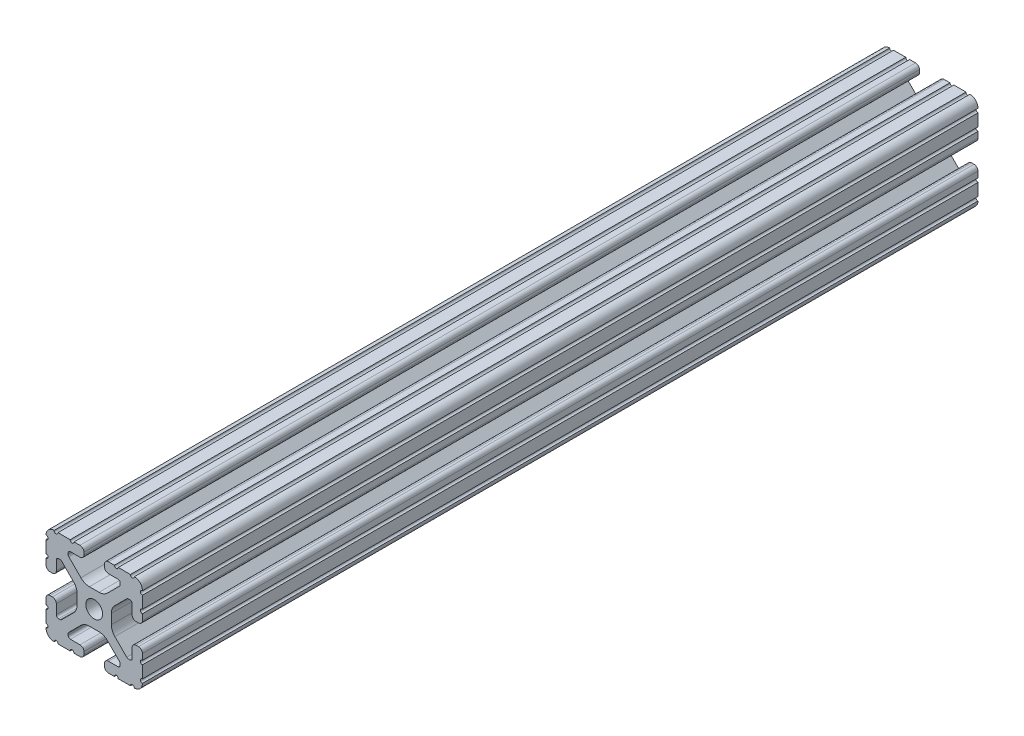
SolidWorks part; units mm, degrees
material "6061 Alloy"
ref_plane "Front Plane" through (0, 0, 0) normal (0, 0, 1) x (1, 0, 0)
ref_plane "Top Plane" through (0, 0, 0) normal (0, 1, 0) x (1, 0, 0)
ref_plane "Right Plane" through (0, 0, 0) normal (1, 0, 0) x (0, 0, -1)
sketch "Sketch1" plane through (0, 0, 0) normal (0, 0, 1) x (1, 0, 0)
  line L0 (0, 25.6181) -> (0, -24.623) construction
  line L1 (-20.8943, 0) -> (20.4607, 0) construction
  line L2 (-10.0229, 12.9148) -> (-5.2522, 8.144)
  line L3 (-10.287, 14.0843) -> (-10.287, 13.5524)
  line L4 (-5.6176, 14.986) -> (-9.3853, 14.986)
  line L5 (-4.064, 17.4964) -> (-4.064, 16.5396)
  line L6 (-7.9742, 19.05) -> (-5.6176, 19.05)
  line L7 (-14.3277, 19.05) -> (-9.4982, 19.05)
  line L8 (-19.05, 9.4961) -> (-19.05, 14.3277)
  line L9 (-19.05, 5.6176) -> (-19.05, 7.9763)
  line L10 (-16.5396, 4.064) -> (-17.4964, 4.064)
  line L11 (-14.986, 9.3853) -> (-14.986, 5.6176)
  line L12 (-13.516, 10.287) -> (-14.0843, 10.287)
  line L13 (-8.1476, 5.2921) -> (-12.8784, 10.0229)
  line L14 (-6.7564, -1.9335) -> (-6.7564, 1.9335)
  line L15 (-12.8784, -10.0229) -> (-8.1476, -5.2921)
  line L16 (-14.0843, -10.287) -> (-13.516, -10.287)
  line L17 (-14.986, -5.6176) -> (-14.986, -9.3853)
  line L18 (-17.4964, -4.064) -> (-16.5396, -4.064)
  line L19 (-19.05, -7.9763) -> (-19.05, -5.6176)
  line L20 (-19.05, -14.3277) -> (-19.05, -9.4961)
  line L21 (-9.4961, -19.05) -> (-14.3277, -19.05)
  line L22 (-5.6176, -19.05) -> (-7.9763, -19.05)
  line L23 (-4.064, -17.4964) -> (-4.064, -16.5396)
  line L24 (10.0229, -12.9148) -> (5.2522, -8.144)
  line L25 (10.287, -14.0843) -> (10.287, -13.5524)
  line L26 (5.6176, -14.986) -> (9.3853, -14.986)
  line L28 (-1.9022, 6.7564) -> (1.9022, 6.7564)
  line L29 (-1.9022, -6.7564) -> (1.9022, -6.7564)
  line L31 (-5.6176, -14.986) -> (-9.3853, -14.986)
  line L32 (-10.287, -14.0843) -> (-10.287, -13.5524)
  line L33 (-10.0229, -12.9148) -> (-5.2522, -8.144)
  line L66 (4.064, -16.5396) -> (4.064, -17.4964)
  line L67 (5.6176, -19.05) -> (7.9763, -19.05)
  line L68 (9.4961, -19.05) -> (14.3277, -19.05)
  line L69 (19.05, -14.3277) -> (19.05, -9.4961)
  line L70 (19.05, -7.9763) -> (19.05, -5.6176)
  line L71 (17.4964, -4.064) -> (16.5396, -4.064)
  line L72 (14.986, -5.6176) -> (14.986, -9.3853)
  line L73 (14.0843, -10.287) -> (13.516, -10.287)
  line L74 (12.8784, -10.0229) -> (8.1476, -5.2921)
  line L75 (6.7564, -1.9335) -> (6.7564, 1.9335)
  line L76 (8.1476, 5.2921) -> (12.8784, 10.0229)
  line L77 (13.516, 10.287) -> (14.0843, 10.287)
  line L78 (14.986, 9.3853) -> (14.986, 5.6176)
  line L79 (16.5396, 4.064) -> (17.4964, 4.064)
  line L80 (19.05, 5.6176) -> (19.05, 7.9763)
  line L81 (19.05, 9.4961) -> (19.05, 14.3277)
  line L82 (14.3277, 19.05) -> (9.4982, 19.05)
  line L83 (7.9742, 19.05) -> (5.6176, 19.05)
  line L84 (4.064, 17.4964) -> (4.064, 16.5396)
  line L85 (5.6176, 14.986) -> (9.3853, 14.986)
  line L86 (10.287, 14.0843) -> (10.287, 13.5524)
  line L87 (10.0229, 12.9148) -> (5.2522, 8.144)
  arc A0 (-10.0229, 12.9148) -> (-10.287, 13.5524) centre (-9.3853, 13.5524) cw
  circle A1 centre (0, 0) radius 3.3274
  arc A2 (-10.287, 14.0843) -> (-9.3853, 14.986) centre (-9.3853, 14.0843) cw
  arc A3 (-4.064, 16.5396) -> (-5.6176, 14.986) centre (-5.6176, 16.5396) cw
  arc A4 (-5.6176, 19.05) -> (-4.064, 17.4964) centre (-5.6176, 17.4964) cw
  arc A5 (-7.9742, 19.05) -> (-9.4982, 19.05) centre (-8.7362, 19.05) cw
  arc A6 (-14.3277, 19.05) -> (-15.8475, 19.05) centre (-15.0876, 18.9933) cw
  arc A7 (-19.05, 15.8475) -> (-15.8475, 19.05) centre (-15.8751, 15.8751) cw
  arc A8 (-19.05, 15.8475) -> (-19.05, 14.3277) centre (-18.9933, 15.0876) cw
  arc A9 (-19.05, 9.4961) -> (-19.05, 7.9763) centre (-18.9933, 8.7362) cw
  arc A10 (-17.4964, 4.064) -> (-19.05, 5.6176) centre (-17.4964, 5.6176) cw
  arc A11 (-14.986, 5.6176) -> (-16.5396, 4.064) centre (-16.5396, 5.6176) cw
  arc A12 (-14.986, 9.3853) -> (-14.0843, 10.287) centre (-14.0843, 9.3853) cw
  arc A13 (-13.516, 10.287) -> (-12.8784, 10.0229) centre (-13.516, 9.3853) cw
  arc A14 (-8.1476, 5.2921) -> (-6.7564, 1.9335) centre (-11.5062, 1.9335) cw
  arc A15 (-6.7564, -1.9335) -> (-8.1476, -5.2921) centre (-11.5062, -1.9335) cw
  arc A16 (-12.8784, -10.0229) -> (-13.516, -10.287) centre (-13.516, -9.3853) cw
  arc A17 (-14.0843, -10.287) -> (-14.986, -9.3853) centre (-14.0843, -9.3853) cw
  arc A18 (-16.5396, -4.064) -> (-14.986, -5.6176) centre (-16.5396, -5.6176) cw
  arc A19 (-19.05, -5.6176) -> (-17.4964, -4.064) centre (-17.4964, -5.6176) cw
  arc A20 (-19.05, -7.9763) -> (-19.05, -9.4961) centre (-18.9933, -8.7362) cw
  arc A21 (-19.05, -14.3277) -> (-19.05, -15.8475) centre (-18.9933, -15.0876) cw
  arc A22 (-15.8475, -19.05) -> (-19.05, -15.8475) centre (-15.8751, -15.8751) cw
  arc A23 (-15.8475, -19.05) -> (-14.3277, -19.05) centre (-15.0876, -18.9933) cw
  arc A24 (-9.4961, -19.05) -> (-7.9763, -19.05) centre (-8.7362, -18.9933) cw
  arc A25 (-4.064, -17.4964) -> (-5.6176, -19.05) centre (-5.6176, -17.4964) cw
  arc A26 (-5.2522, -8.144) -> (-1.9022, -6.7564) centre (-1.9022, -11.494) cw
  arc A27 (1.9022, -6.7564) -> (5.2522, -8.144) centre (1.9022, -11.494) cw
  arc A28 (10.0229, -12.9148) -> (10.287, -13.5524) centre (9.3853, -13.5524) cw
  arc A29 (10.287, -14.0843) -> (9.3853, -14.986) centre (9.3853, -14.0843) cw
  arc A30 (4.064, -16.5396) -> (5.6176, -14.986) centre (5.6176, -16.5396) cw
  arc A31 (-4.064, -16.5396) -> (-5.6176, -14.986) centre (-5.6176, -16.5396) ccw
  arc A32 (-10.287, -14.0843) -> (-9.3853, -14.986) centre (-9.3853, -14.0843) ccw
  arc A33 (-10.0229, -12.9148) -> (-10.287, -13.5524) centre (-9.3853, -13.5524) ccw
  arc A79 (4.064, -17.4964) -> (5.6176, -19.05) centre (5.6176, -17.4964) ccw
  arc A80 (9.4961, -19.05) -> (7.9763, -19.05) centre (8.7362, -18.9933) ccw
  arc A81 (15.8475, -19.05) -> (14.3277, -19.05) centre (15.0876, -18.9933) ccw
  arc A82 (15.8475, -19.05) -> (19.05, -15.8475) centre (15.8751, -15.8751) ccw
  arc A83 (19.05, -14.3277) -> (19.05, -15.8475) centre (18.9933, -15.0876) ccw
  arc A84 (19.05, -7.9763) -> (19.05, -9.4961) centre (18.9933, -8.7362) ccw
  arc A85 (19.05, -5.6176) -> (17.4964, -4.064) centre (17.4964, -5.6176) ccw
  arc A86 (16.5396, -4.064) -> (14.986, -5.6176) centre (16.5396, -5.6176) ccw
  arc A87 (14.0843, -10.287) -> (14.986, -9.3853) centre (14.0843, -9.3853) ccw
  arc A88 (12.8784, -10.0229) -> (13.516, -10.287) centre (13.516, -9.3853) ccw
  arc A89 (6.7564, -1.9335) -> (8.1476, -5.2921) centre (11.5062, -1.9335) ccw
  arc A90 (8.1476, 5.2921) -> (6.7564, 1.9335) centre (11.5062, 1.9335) ccw
  arc A91 (13.516, 10.287) -> (12.8784, 10.0229) centre (13.516, 9.3853) ccw
  arc A92 (14.986, 9.3853) -> (14.0843, 10.287) centre (14.0843, 9.3853) ccw
  arc A93 (14.986, 5.6176) -> (16.5396, 4.064) centre (16.5396, 5.6176) ccw
  arc A94 (17.4964, 4.064) -> (19.05, 5.6176) centre (17.4964, 5.6176) ccw
  arc A95 (19.05, 9.4961) -> (19.05, 7.9763) centre (18.9933, 8.7362) ccw
  arc A96 (19.05, 15.8475) -> (19.05, 14.3277) centre (18.9933, 15.0876) ccw
  arc A97 (19.05, 15.8475) -> (15.8475, 19.05) centre (15.8751, 15.8751) ccw
  arc A98 (14.3277, 19.05) -> (15.8475, 19.05) centre (15.0876, 18.9933) ccw
  arc A99 (7.9742, 19.05) -> (9.4982, 19.05) centre (8.7362, 19.05) ccw
  arc A100 (5.6176, 19.05) -> (4.064, 17.4964) centre (5.6176, 17.4964) ccw
  arc A101 (4.064, 16.5396) -> (5.6176, 14.986) centre (5.6176, 16.5396) ccw
  arc A102 (10.287, 14.0843) -> (9.3853, 14.986) centre (9.3853, 14.0843) ccw
  arc A103 (10.0229, 12.9148) -> (10.287, 13.5524) centre (9.3853, 13.5524) ccw
  arc A104 (1.9022, 6.7564) -> (5.2522, 8.144) centre (1.9022, 11.494) ccw
  arc A105 (-5.2522, 8.144) -> (-1.9022, 6.7564) centre (-1.9022, 11.494) ccw
  dimension "D1" = 6.6548
  dimension "D2" = 19.05
  dimension "D3" = 38.1
  dimension "D4" = 20.574
  dimension "D5" = 13.5128
  dimension "D6" = 4.064
  dimension "D7" = 8.128
  dimension "D8" = 4.064
  dimension "D9" = 12.2936
extrude "Extrude1" add sketch "Sketch1" against normal blind 330.2
